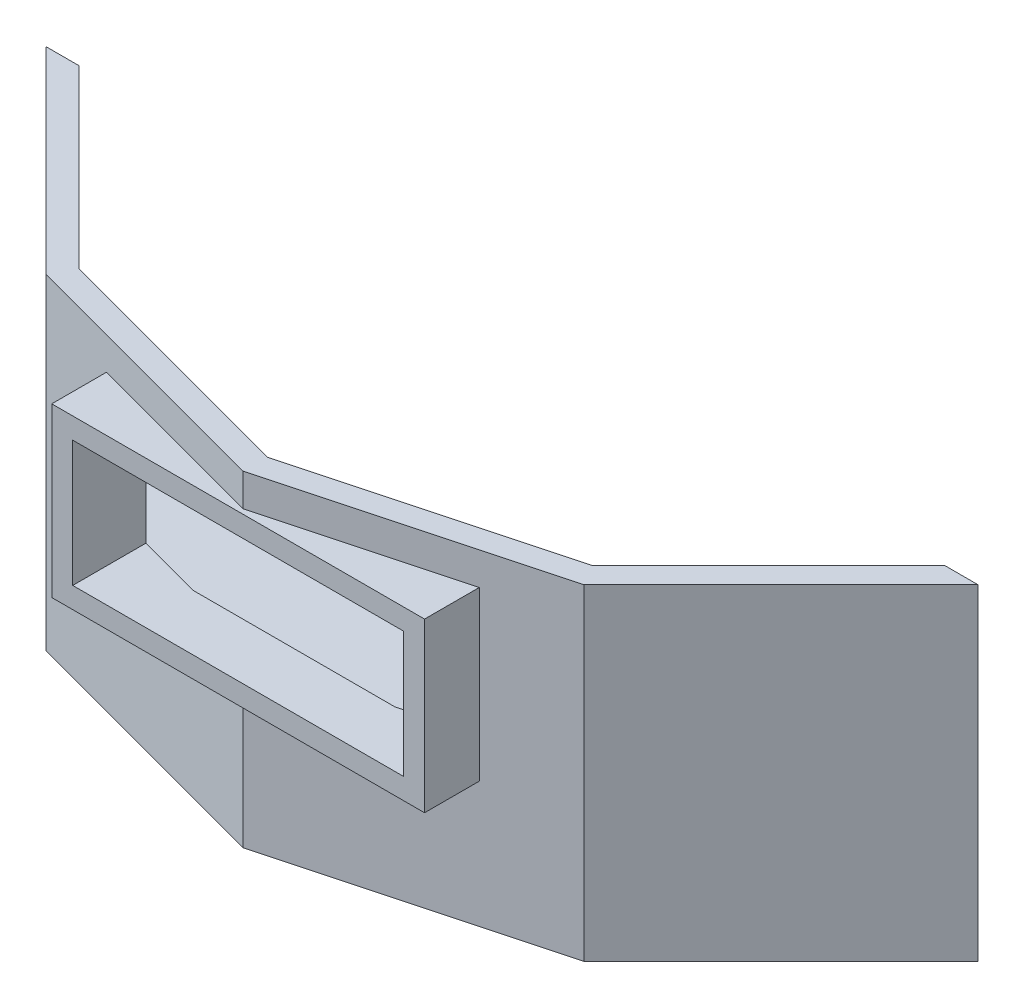
SolidWorks part; units mm, degrees
ref_plane "Front Plane" through (0, 0, 0) normal (0, 0, 1) x (1, 0, 0)
ref_plane "Top Plane" through (0, 0, 0) normal (0, 1, 0) x (1, 0, 0)
ref_plane "Right Plane" through (0, 0, 0) normal (1, 0, 0) x (0, 0, -1)
sketch "Sketch1" plane through (0, 0, 0) normal (0, 1, 0) x (1, 0, 0)
  line L0 (57.735, -100) -> (100, -57.735)
  line L14 (-100, -57.735) -> (-57.735, -100)
  line L15 (-57.735, -100) -> (0, -115.4701)
  line L16 (0, -115.4701) -> (57.735, -100)
  line L18 (-100, -57.735) -> (100, -57.735)
  line L23 (107.735, -28.8675) -> (115.4701, 0) [skipped]
  line L24 (-115.4701, 0) -> (-107.735, -28.8675) [skipped]
  line L25 (-100, 57.735) -> (-107.735, 28.8675) [skipped]
  line L26 (100, 57.735) -> (78.8675, 78.8675) [skipped]
  line L27 (115.4701, 0) -> (100, 57.735) [skipped]
  line L28 (28.8675, 107.735) -> (0, 115.4701) [skipped]
  line L29 (0, 115.4701) -> (-28.8675, 107.735) [skipped]
  line L30 (-57.735, 100) -> (-78.8675, 78.8675) [skipped]
  arc A1 (-95.4297, -57.735) -> (95.4297, -57.735) centre (0, 0) ccw construction
  dimension "D1" = 200
  dimension "D2" = 57.735
extrude "Boss-Extrude1" add sketch "Sketch1" along normal blind 70
sketch "Sketch4" plane through (0, 70, 0) normal (0, 1, 0) x (1, 0, 0)
  line L1 (110.2937, 0) -> (95.5171, 55.1468)
  line L2 (95.5171, 55.1468) -> (55.1468, 95.5171)
  line L3 (55.1468, 95.5171) -> (0, 110.2937)
  line L4 (0, 110.2937) -> (-55.1468, 95.5171)
  line L5 (-55.1468, 95.5171) -> (-95.5171, 55.1468)
  line L6 (-95.5171, 55.1468) -> (-110.2937, 0)
  line L7 (-110.2937, 0) -> (-95.5171, -55.1468)
  line L8 (-95.5171, -55.1468) -> (-55.1468, -95.5171)
  line L9 (-55.1468, -95.5171) -> (0, -110.2937)
  line L10 (0, -110.2937) -> (55.1468, -95.5171)
  line L11 (55.1468, -95.5171) -> (95.5171, -55.1468)
  line L12 (95.5171, -55.1468) -> (110.2937, 0)
  line L13 (-57.735, -100) -> (0, -115.4701) construction
  circle A0 centre (0, 0) radius 106.5355 construction
  dimension "D1" = 5
extrude "Cut-Extrude1" cut sketch "Sketch4" against normal blind 65
ref_plane "Plane1" through (0, 0, 104.5) normal (0, 0, 1) x (1, 0, 0)
sketch "Sketch6" plane through (0, 0, 104.5) normal (0, 0, 1) x (1, 0, 0)
  line L0 (-100, 70) -> (-100, 0) construction
  line L1 (-40, 63) -> (40, 63)
  line L2 (-40, 63) -> (-40, 27)
  line L3 (-40, 27) -> (40, 27)
  line L4 (40, 63) -> (40, 27)
  line L5 (-40, 63) -> (40, 27) construction
  line L6 (-40, 27) -> (40, 63) construction
  line L7 (0, 0) -> (57.735, 0) construction
  point P4 (0, 45)
  dimension "D1" = 80
  dimension "D2" = 36
  dimension "D3" = 100
  dimension "D4" = 45
extrude "Boss-Extrude2" add sketch "Sketch6" along normal blind 12
sketch "Sketch7" plane through (0, 0, 116.5) normal (0, 0, 1) x (1, 0, 0)
  line L0 (-57.735, 0) -> (0, 0) construction
  line L1 (-35.5, 58.5) -> (35.5, 58.5)
  line L2 (-35.5, 58.5) -> (-35.5, 31.5)
  line L3 (-35.5, 31.5) -> (35.5, 31.5)
  line L4 (35.5, 58.5) -> (35.5, 31.5)
  line L5 (-35.5, 58.5) -> (35.5, 31.5) construction
  line L6 (-35.5, 31.5) -> (35.5, 58.5) construction
  line L8 (-100, 70) -> (-100, 0) construction
  point P4 (0, 45)
  point P9 (-65.5319, 12.611)
  dimension "D1" = 71
  dimension "D2" = 27
  dimension "D3" = 45
  dimension "D4" = 100
extrude "Cut-Extrude2" cut sketch "Sketch7" against normal blind 20
